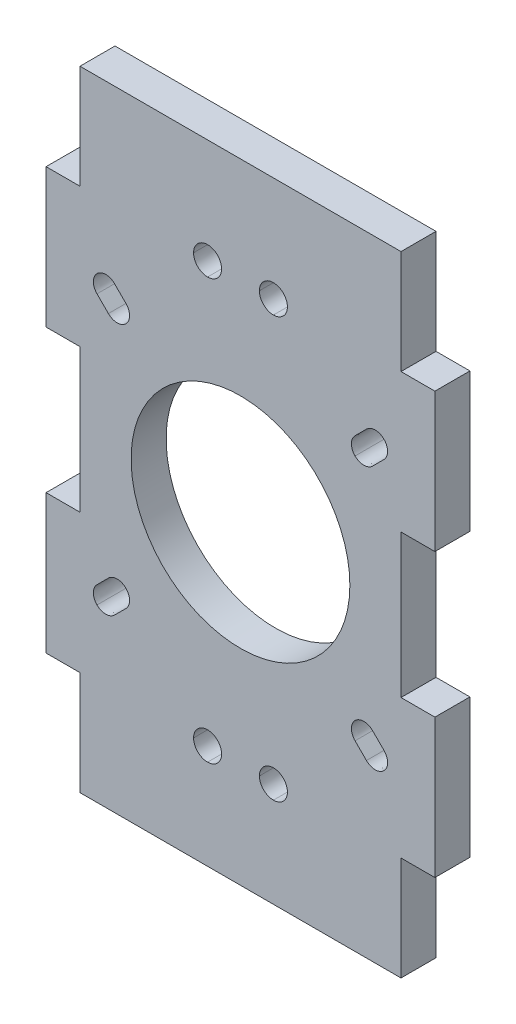
SolidWorks part; units mm, degrees
ref_plane "Front Plane" through (0, 0, 0) normal (0, 0, 1) x (1, 0, 0)
ref_plane "Top Plane" through (0, 0, 0) normal (0, 1, 0) x (1, 0, 0)
ref_plane "Right Plane" through (0, 0, 0) normal (1, 0, 0) x (0, 0, -1)
sketch "Model" plane through (0, 0, 0) normal (0, 0, 1) x (1, 0, 0)
  line L206 (-20.5954, 132.4124) -> (-26.7451, 132.4124)
  line L207 (-26.7451, 132.4124) -> (-26.7451, 151.262)
  line L208 (-26.7451, 151.262) -> (-84.9649, 151.262)
  line L209 (-84.9649, 151.262) -> (-84.9649, 132.4124)
  line L210 (-84.9649, 132.4124) -> (-91.1147, 132.4124)
  line L211 (-91.1147, 132.4124) -> (-91.1147, 107.2136)
  line L212 (-91.1147, 107.2136) -> (-84.9649, 107.2136)
  line L213 (-84.9649, 107.2136) -> (-84.9649, 81.2129)
  line L214 (-84.9649, 81.2129) -> (-91.1147, 81.2129)
  line L215 (-91.1147, 81.2129) -> (-91.1147, 56.0124)
  line L216 (-91.1147, 56.0124) -> (-84.9649, 56.0124)
  line L217 (-84.9649, 56.0124) -> (-84.9649, 37.1628)
  line L218 (-84.9649, 37.1628) -> (-26.7451, 37.1628)
  line L219 (-26.7451, 37.1628) -> (-26.7451, 56.0124)
  line L220 (-26.7451, 56.0124) -> (-20.5954, 56.0124)
  line L221 (-20.5954, 56.0124) -> (-20.5954, 81.2129)
  line L222 (-20.5954, 81.2129) -> (-26.7451, 81.2129)
  line L223 (-26.7451, 81.2129) -> (-26.7451, 107.2136)
  line L224 (-26.7451, 107.2136) -> (-20.5954, 107.2136)
  line L225 (-20.5954, 107.2136) -> (-20.5954, 132.4124)
  line L226 (-76.6319, 70.2547) -> (-78.6976, 68.1899)
  line L227 (-81.878, 71.3707) -> (-79.8123, 73.4364)
  line L228 (-29.8321, 117.0554) -> (-31.897, 114.9897)
  line L229 (-35.0782, 118.1705) -> (-33.0129, 120.2357)
  line L230 (-29.8321, 71.3707) -> (-31.8965, 73.4364)
  line L231 (-35.0786, 70.2543) -> (-33.0129, 68.1899)
  line L232 (-76.6319, 118.1705) -> (-78.6976, 120.2357)
  line L233 (-81.878, 117.0554) -> (-79.8127, 114.9897)
  circle A0 centre (-55.8552, 94.2124) radius 19.8387
  spline S444 degree 3 poles (-61.8264, 129.7262) (-60.4231, 129.7262) (-59.2852, 130.8633) (-59.2852, 132.2662) knots 0 0 0 0 0.2 0.2 0.2 0.2
  spline S445 degree 3 poles (-59.2852, 132.2662) (-59.2852, 133.6691) (-60.4231, 134.8074) (-61.8264, 134.8074) knots 0.2 0.2 0.2 0.2 0.4 0.4 0.4 0.4
  spline S446 degree 3 poles (-61.8264, 134.8074) (-63.2289, 134.8074) (-64.366, 133.6691) (-64.366, 132.2662) knots 0.4 0.4 0.4 0.4 0.6 0.6 0.6 0.6
  spline S447 degree 3 poles (-64.366, 132.2662) (-64.366, 130.8633) (-63.2289, 129.7262) (-61.8264, 129.7262) knots 0.6 0.6 0.6 0.6 1 1 1 1
  spline S448 degree 3 poles (-61.8264, 53.5264) (-60.4231, 53.5264) (-59.2852, 54.6635) (-59.2852, 56.0664) knots 0 0 0 0 0.2 0.2 0.2 0.2
  spline S449 degree 3 poles (-59.2852, 56.0664) (-59.2852, 57.4693) (-60.4231, 58.6076) (-61.8264, 58.6076) knots 0.2 0.2 0.2 0.2 0.4 0.4 0.4 0.4
  spline S450 degree 3 poles (-61.8264, 58.6076) (-63.2289, 58.6076) (-64.366, 57.4693) (-64.366, 56.0664) knots 0.4 0.4 0.4 0.4 0.6 0.6 0.6 0.6
  spline S451 degree 3 poles (-64.366, 56.0664) (-64.366, 54.6635) (-63.2289, 53.5264) (-61.8264, 53.5264) knots 0.6 0.6 0.6 0.6 1 1 1 1
  spline S452 degree 3 poles (-78.6976, 68.1899) (-79.578, 67.3086) (-80.9971, 67.3086) (-81.878, 68.1903) knots 0.142857 0.142857 0.142857 0.142857 0.285714 0.285714 0.285714 0.285714
  spline S453 degree 3 poles (-81.878, 68.1903) (-82.7596, 69.0707) (-82.7601, 70.4902) (-81.878, 71.3707) knots 0.285714 0.285714 0.285714 0.285714 0.428571 0.428571 0.428571 0.428571
  spline S454 degree 3 poles (-79.8123, 73.4364) (-78.9314, 74.3172) (-77.5119, 74.3172) (-76.6315, 73.4364) knots 0.571429 0.571429 0.571429 0.571429 0.714286 0.714286 0.714286 0.714286
  spline S455 degree 3 poles (-76.6315, 73.4364) (-75.7498, 72.5547) (-75.7498, 71.1368) (-76.6319, 70.2547) knots 0.714286 0.714286 0.714286 0.714286 1 1 1 1
  spline S456 degree 3 poles (-31.897, 114.9897) (-32.7791, 114.1076) (-34.1965, 114.1076) (-35.0782, 114.9897) knots 0.142857 0.142857 0.142857 0.142857 0.285714 0.285714 0.285714 0.285714
  spline S457 degree 3 poles (-35.0782, 114.9897) (-35.959, 115.8705) (-35.959, 117.2896) (-35.0782, 118.1705) knots 0.285714 0.285714 0.285714 0.285714 0.428571 0.428571 0.428571 0.428571
  spline S458 degree 3 poles (-33.0129, 120.2357) (-32.1324, 121.1178) (-30.7129, 121.1178) (-29.8321, 120.2357) knots 0.571429 0.571429 0.571429 0.571429 0.714286 0.714286 0.714286 0.714286
  spline S459 degree 3 poles (-29.8321, 120.2357) (-28.95, 119.3553) (-28.9504, 117.9362) (-29.8321, 117.0554) knots 0.714286 0.714286 0.714286 0.714286 1 1 1 1
  spline S460 degree 3 poles (-31.8965, 73.4364) (-32.7786, 74.3172) (-34.1969, 74.3172) (-35.0786, 73.4364) knots 0.142857 0.142857 0.142857 0.142857 0.285714 0.285714 0.285714 0.285714
  spline S461 degree 3 poles (-35.0786, 73.4364) (-35.959, 72.5547) (-35.959, 71.1364) (-35.0786, 70.2543) knots 0.285714 0.285714 0.285714 0.285714 0.428571 0.428571 0.428571 0.428571
  spline S462 degree 3 poles (-33.0129, 68.1899) (-32.1324, 67.3082) (-30.7129, 67.3086) (-29.8325, 68.1903) knots 0.571429 0.571429 0.571429 0.571429 0.714286 0.714286 0.714286 0.714286
  spline S463 degree 3 poles (-29.8325, 68.1903) (-28.9504, 69.0707) (-28.95, 70.4902) (-29.8321, 71.3707) knots 0.714286 0.714286 0.714286 0.714286 1 1 1 1
  spline S464 degree 3 poles (-78.6976, 120.2357) (-79.578, 121.1178) (-80.9975, 121.1178) (-81.878, 120.2357) knots 0.142857 0.142857 0.142857 0.142857 0.285714 0.285714 0.285714 0.285714
  spline S465 degree 3 poles (-81.878, 120.2357) (-82.7601, 119.3553) (-82.7601, 117.9358) (-81.878, 117.0554) knots 0.285714 0.285714 0.285714 0.285714 0.428571 0.428571 0.428571 0.428571
  spline S466 degree 3 poles (-79.8127, 114.9897) (-78.9322, 114.1076) (-77.5123, 114.1076) (-76.6319, 114.9897) knots 0.571429 0.571429 0.571429 0.571429 0.714286 0.714286 0.714286 0.714286
  spline S467 degree 3 poles (-76.6319, 114.9897) (-75.7498, 115.8705) (-75.7498, 117.29) (-76.6319, 118.1705) knots 0.714286 0.714286 0.714286 0.714286 1 1 1 1
  spline S468 degree 3 poles (-49.884, 129.7262) (-48.4812, 129.7262) (-47.3445, 130.8633) (-47.3445, 132.2662) knots 0 0 0 0 0.2 0.2 0.2 0.2
  spline S469 degree 3 poles (-47.3445, 132.2662) (-47.3445, 133.6691) (-48.4812, 134.8074) (-49.884, 134.8074) knots 0.2 0.2 0.2 0.2 0.4 0.4 0.4 0.4
  spline S470 degree 3 poles (-49.884, 134.8074) (-51.2869, 134.8074) (-52.424, 133.6691) (-52.424, 132.2662) knots 0.4 0.4 0.4 0.4 0.6 0.6 0.6 0.6
  spline S471 degree 3 poles (-52.424, 132.2662) (-52.424, 130.8633) (-51.2869, 129.7262) (-49.884, 129.7262) knots 0.6 0.6 0.6 0.6 1 1 1 1
  spline S472 degree 3 poles (-49.884, 53.5264) (-48.4812, 53.5264) (-47.3445, 54.6635) (-47.3445, 56.0664) knots 0 0 0 0 0.2 0.2 0.2 0.2
  spline S473 degree 3 poles (-47.3445, 56.0664) (-47.3445, 57.4693) (-48.4812, 58.6076) (-49.884, 58.6076) knots 0.2 0.2 0.2 0.2 0.4 0.4 0.4 0.4
  spline S474 degree 3 poles (-49.884, 58.6076) (-51.2869, 58.6076) (-52.424, 57.4693) (-52.424, 56.0664) knots 0.4 0.4 0.4 0.4 0.6 0.6 0.6 0.6
  spline S475 degree 3 poles (-52.424, 56.0664) (-52.424, 54.6635) (-51.2869, 53.5264) (-49.884, 53.5264) knots 0.6 0.6 0.6 0.6 1 1 1 1
extrude "Boss-Extrude1" add sketch "Model" along normal blind 6.35
